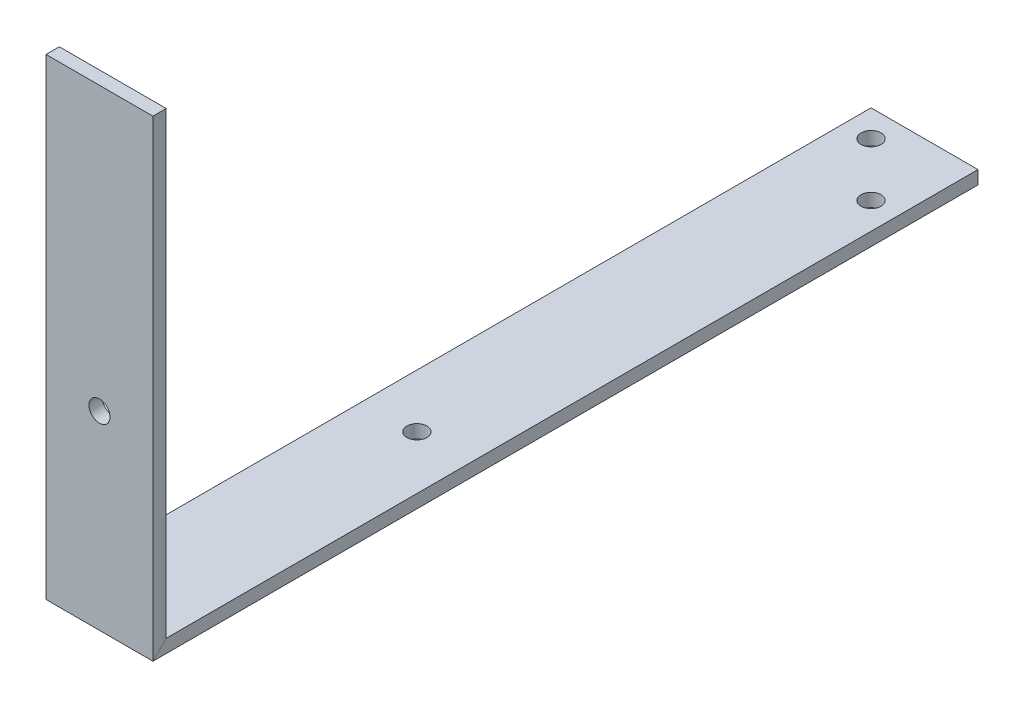
SolidWorks part; units mm, degrees
ref_plane "Alzado" through (0, 0, 0) normal (0, 0, 1) x (1, 0, 0)
ref_plane "Planta" through (0, 0, 0) normal (0, 1, 0) x (1, 0, 0)
ref_plane "Vista lateral" through (0, 0, 0) normal (1, 0, 0) x (0, 0, -1)
sketch "Croquis2" plane through (0, 0, 0) normal (0, 1, 0) x (1, 0, 0)
  line L1 (-25.4, 3.155) -> (25.4, 3.155)
  line L2 (-25.4, 3.155) -> (-25.4, -3.155)
  line L3 (-25.4, -3.155) -> (25.4, -3.155)
  line L4 (25.4, 3.155) -> (25.4, -3.155)
  line L5 (-25.4, 3.155) -> (25.4, -3.155) construction
  line L6 (-25.4, -3.155) -> (25.4, 3.155) construction
  line L7 (184.6, 3.155) -> (235.4, 3.155)
  line L8 (184.6, 3.155) -> (184.6, -3.155)
  line L9 (184.6, -3.155) -> (235.4, -3.155)
  line L10 (235.4, 3.155) -> (235.4, -3.155)
  line L11 (184.6, 3.155) -> (235.4, -3.155) construction
  line L12 (184.6, -3.155) -> (235.4, 3.155) construction
  point P0 (0, 0)
  point P6 (210, 0)
  dimension "D1" = 50.8
  dimension "D2" = 6.31
  dimension "D3" = 210
  dimension "D4" = 50.8
  dimension "D5" = 6.31
sketch3d "Croquis3D1"
  line L0 (0, 0, 0) -> (0, -567.24, 0)
  line L1 (0, -567.24, 0) -> (0, -567.24, 336.2)
  line L2 (0, -567.24, 336.2) -> (1786.7, -567.24, 336.2)
  line L3 (1786.7, -567.24, 336.2) -> (1786.7, -567.24, 693.16)
  line L4 (-25.4, 0, 0) -> (-25.4, -383.9185, 0) construction
  line L5 (-25.4, 0, -3.155) -> (-25.4, 0, 3.155) construction
  line L6 (-25.4, -383.9185, 0) -> (-25.4, -383.9185, 653.2834) construction
  line L7 (1786.7, -567.24, 693.16) -> (1786.7, -436.23, 693.16)
  line L8 (1786.7, -436.23, 693.16) -> (1786.7, -436.23, 1487.1629)
  dimension "D1" = 567.24
  dimension "D2" = 336.2
  dimension "D3" = 1786.7
  dimension "D4" = 356.96
  dimension "D5" = 131.01
  dimension "D6" = 794.0029
sweep "Barrer1" add profiles "Croquis2" path "Croquis3D1"
sketch "Croquis3" plane through (0, 0, -3.155) normal (0, 0, -1) x (-1, 0, 0)
  line L0 (-235.4, 0) -> (-235.4, -6.31)
  line L1 (-235.4, 0) -> (-235.4, -570.395) construction
  line L2 (-235.4, -6.31) -> (-184.6, -6.31)
  line L3 (-184.6, 0) -> (-184.6, -570.395) construction
  line L4 (-184.6, -6.31) -> (-184.6, 0)
  line L5 (-184.6, 0) -> (-235.4, 0)
  line L7 (-25.4, 0) -> (-25.4, -6.31)
  line L8 (-25.4, 0) -> (-25.4, -570.395) construction
  line L9 (-25.4, -6.31) -> (25.4, -6.31)
  line L10 (25.4, 0) -> (25.4, -570.395) construction
  line L11 (25.4, -6.31) -> (25.4, 0)
  line L12 (-25.4, 0) -> (25.4, 0) construction
  line L13 (25.4, 0) -> (-25.4, 0)
  dimension "D1" = 6.31
  dimension "D2" = 6.31
sketch3d "Croquis3D2"
  line L0 (25.4, -3.155, -3.155) -> (-0.201, -3.155, -3.155) construction
  line L1 (25.4, 0, -3.155) -> (25.4, -6.31, -3.155) construction
  line L2 (-0.201, -3.155, -3.155) -> (-0.201, -5.2746, -3.155) construction
  line L3 (-0.201, -3.155, -3.155) -> (-0.201, -3.155, -207.155)
  line L4 (-0.201, -3.155, -207.155) -> (-0.201, -53.155, -207.155)
  dimension "D1" = 204
  dimension "D2" = 50
sweep "Barrer4" add profiles "Croquis3" path "Croquis3D2"
sketch "Croquis4" plane through (0, 0, -210.31) normal (0, 0, -1) x (-1, 0, 0)
  line L0 (-184.6, 0) -> (-184.6, -53.155)
  line L1 (-184.6, -53.155) -> (-124.6, -53.155)
  line L2 (-124.6, -53.155) -> (-124.6, 0)
  line L3 (-124.6, 0) -> (-184.6, 0)
  dimension "D1" = 60
extrude "Saliente-Extruir1" add sketch "Croquis4" against normal blind 6.31
sketch "Croquis5" plane through (0, 0, -204) normal (0, 0, 1) x (1, 0, 0)
  line L0 (184.6, -6.31) -> (124.6, -6.31)
  line L1 (124.6, -53.155) -> (124.6, 0) construction
  line L2 (124.6, -6.31) -> (124.6, 0)
  line L3 (124.6, 0) -> (184.6, 0)
  line L4 (184.6, 0) -> (184.6, -6.31)
extrude "Cortar-Extruir1" cut sketch "Croquis5" against normal blind 6.31
sketch "Croquis6" plane through (0, -433.075, 0) normal (0, 1, 0) x (1, 0, 0)
  circle A0 centre (1285.7, -1260.295) radius 4.75
  circle A1 centre (1495.7, -1260.295) radius 4.75
sketch "Croquis7" plane through (0, 0, 0) normal (0, 1, 0) x (1, 0, 0)
  line L0 (1761.3, -361.6) -> (2022.1, -361.6)
  line L1 (2022.1, -100.8) -> (2022.1, -690.005) construction
  line L2 (2022.1, -361.6) -> (2022.1, 278.6006)
  line L3 (2022.1, 278.6006) -> (-188.1159, 278.6006)
  line L4 (-188.1159, 278.6006) -> (-188.1159, -361.6)
  line L5 (-188.1159, -361.6) -> (1761.3, -361.6)
extrude "Cortar-Extruir2" cut sketch "Croquis7" against normal blind 634
sketch "Croquis8" plane through (0, 0, 361.6) normal (0, 0, -1) x (-1, 0, 0)
  line L0 (-1812.1, -564.085) -> (-1761.3, -564.085)
  line L1 (-1761.3, -564.085) -> (-1761.3, -570.395)
  line L2 (-1761.3, -570.395) -> (-1812.1, -570.395)
  line L3 (-1812.1, -570.395) -> (-1812.1, -564.085)
extrude "Saliente-Extruir2" add sketch "Croquis8" along normal blind 63.5
sketch "Croquis9" plane through (0, -433.075, 0) normal (0, 1, 0) x (1, 0, 0)
  line L0 (1786.7, -1487.1629) -> (1996.7, -1487.1629) construction
  line L1 (1761.3, -1487.1629) -> (1812.1, -1487.1629) construction
  line L2 (1971.3, -1487.1629) -> (2022.1, -1487.1629) construction
  line L3 (1996.7, -1487.1629) -> (1996.7, -1454.1629) construction
  line L4 (1996.7, -1454.1629) -> (1996.7, -1234.1629) construction
  line L5 (1786.7, -1487.1629) -> (1786.7, -1454.1629) construction
  line L6 (1786.7, -1454.1629) -> (1786.7, -1234.1629) construction
  circle A0 centre (1786.7, -1454.1629) radius 5
  circle A1 centre (1786.7, -1234.1629) radius 5
  circle A2 centre (1996.7, -1234.1629) radius 5
  circle A3 centre (1996.7, -1454.1629) radius 5
  dimension "D3" = 10
  dimension "D4" = 10
  dimension "D5" = 10
  dimension "D6" = 10
  dimension "D1" = 33
  dimension "D2" = 220
extrude "Cortar-Extruir3" cut sketch "Croquis9" against normal blind 10
sketch "Croquis10" plane through (2022.1, 0, 0) normal (1, 0, 0) x (0, 0, -1)
  line L0 (-696.315, -439.385) -> (-696.315, -433.075)
  line L1 (-690.005, -433.075) -> (-1487.1629, -433.075) construction
  line L2 (-696.315, -433.075) -> (-1487.1629, -433.075)
  line L3 (-1487.1629, -433.075) -> (-1487.1629, -439.385)
  line L4 (-1487.1629, -439.385) -> (-696.315, -439.385)
extrude "Cortar-Extruir4" cut sketch "Croquis10" against normal blind 286
sketch "Croquis11" plane through (0, -433.075, 0) normal (0, 1, 0) x (1, 0, 0)
  line L0 (2022.1, -696.315) -> (2022.1, -690.005)
  line L1 (2022.1, -690.005) -> (1761.3, -690.005)
  line L2 (1761.3, -690.005) -> (1761.3, -696.315)
  line L3 (1761.3, -696.315) -> (2022.1, -696.315)
  line L4 (2022.1, -696.315) -> (2028.4123, -762.8726)
  line M1 (1971.3, -690.005) -> (1971.3, -696.315)
  line M2 (1971.3, -696.315) -> (2022.1, -696.315)
  line M3 (2022.1, -696.315) -> (2022.1, -690.005)
  line M4 (2022.1, -690.005) -> (1971.3, -690.005)
extrude "Cortar-Extruir5" cut sketch "Croquis11" against normal blind 13.11 contours M4 M1 M2 M3 | L2 L3 L1 M1
sketch "Croquis12" plane through (0, 0, 361.6) normal (0, 0, -1) x (-1, 0, 0)
  line L0 (-2022.1, -564.085) -> (-2022.1, -570.395)
  line L1 (-2022.1, -570.395) -> (-1971.3, -570.395)
  line L2 (-1971.3, -570.395) -> (-1971.3, -564.085)
  line L3 (-1971.3, -564.085) -> (-2022.1, -564.085)
extrude "Saliente-Extruir3" add sketch "Croquis12" along normal blind 6.35
sketch "Croquis13" plane through (0, -564.085, 0) normal (0, 1, 0) x (1, 0, 0)
  line L0 (1812.1, -298.1) -> (1812.1, -304.45)
  line L1 (1812.1, -298.1) -> (1812.1, -690.005) construction
  line L2 (1812.1, -304.45) -> (1761.3, -304.45)
  line L3 (1761.3, -298.1) -> (1761.3, -690.005) construction
  line L4 (1761.3, -304.45) -> (1761.3, -298.1)
  line L5 (1761.3, -298.1) -> (1812.1, -298.1)
  dimension "D1" = 6.35
extrude "Cortar-Extruir6" cut sketch "Croquis13" against normal blind 6.35
sketch "Croquis14" plane through (0, -446.185, 0) normal (0, 1, 0) x (1, 0, 0)
  line L1 (2042.1777, -334.8977) -> (1956.3306, -334.8977)
  line L2 (2042.1777, -334.8977) -> (2042.1777, -808.5369)
  line L3 (2042.1777, -808.5369) -> (1956.3306, -808.5369)
  line L4 (1956.3306, -334.8977) -> (1956.3306, -808.5369)
  line L5 (2042.1777, -334.8977) -> (1956.3306, -808.5369) construction
  line L6 (2042.1777, -808.5369) -> (1956.3306, -334.8977) construction
  point P0 (1999.2542, -571.7173)
extrude "Cortar-Extruir7" cut sketch "Croquis14" against normal blind 137
sketch "Croquis15" plane through (0, -564.085, 0) normal (0, 1, 0) x (1, 0, 0)
  line L0 (1786.7, -545.545) -> (1788.8858, -549.7763) construction
  line L1 (1788.8858, -549.7763) -> (1786.7, -545.545) construction
  circle A0 centre (1786.7, -545.545) radius 4.7625
extrude "Cortar-Extruir8" cut sketch "Croquis15" against normal blind 33
sketch "Croquis16" plane through (0, 0, 690.005) normal (0, 0, -1) x (-1, 0, 0)
  line L0 (-1786.7, -446.185) -> (-1786.7, -480.185) construction
  line L1 (-1812.1, -446.185) -> (-1761.3, -446.185) construction
  line L2 (-1786.7, -567.24) -> (-1786.7, -436.23) construction
  circle A0 centre (-1786.7, -480.185) radius 5
  dimension "D2" = 10
  dimension "D1" = 34
extrude "Cortar-Extruir9" cut sketch "Croquis16" against normal blind 33
sketch "Croquis18" plane through (0, -570.395, 0) normal (0, -1, 0) x (-1, 0, 0)
  circle A0 centre (-1799.4, -342.5522) radius 4.7625
  circle A1 centre (-1774, -317.1522) radius 4.7625
extrude "Cortar-Extruir10" cut sketch "Croquis18" against normal blind 50
sketch "Croquis19" plane through (0, -446.185, 0) normal (0, 1, 0) x (1, 0, 0)
  line L0 (1761.3, -696.315) -> (1761.3, -690.005)
  line L1 (1761.3, -690.005) -> (1812.1, -690.005)
  line L2 (1812.1, -690.005) -> (1812.1, -696.315)
  line L3 (1812.1, -696.315) -> (1761.3, -696.315)
extrude "Saliente-Extruir4" add sketch "Croquis19" along normal blind 100
